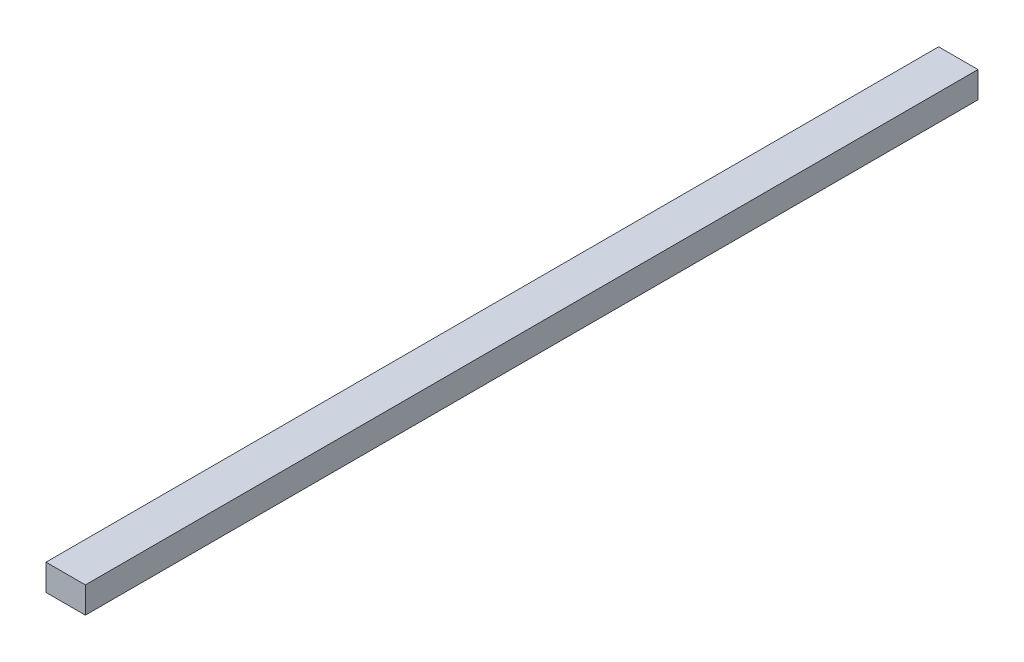
SolidWorks part; units mm, degrees
ref_plane "Front Plane" through (0, 0, 0) normal (0, 0, 1) x (1, 0, 0)
ref_plane "Top Plane" through (0, 0, 0) normal (0, 1, 0) x (1, 0, 0)
ref_plane "Right Plane" through (0, 0, 0) normal (1, 0, 0) x (0, 0, -1)
other "Configuration Table"
sketch "Sketch1" plane through (0, 0, 0) normal (0, 0, 1) x (1, 0, 0)
  line L1 (35, 0) -> (65, 0)
  line L2 (35, 0) -> (35, 20)
  line L3 (35, 20) -> (65, 20)
  line L4 (65, 0) -> (65, 20)
extrude "KAPYAG_kizak_sag_30x20_1" add sketch "Sketch1" against normal blind 680 from offset 20 separate body
